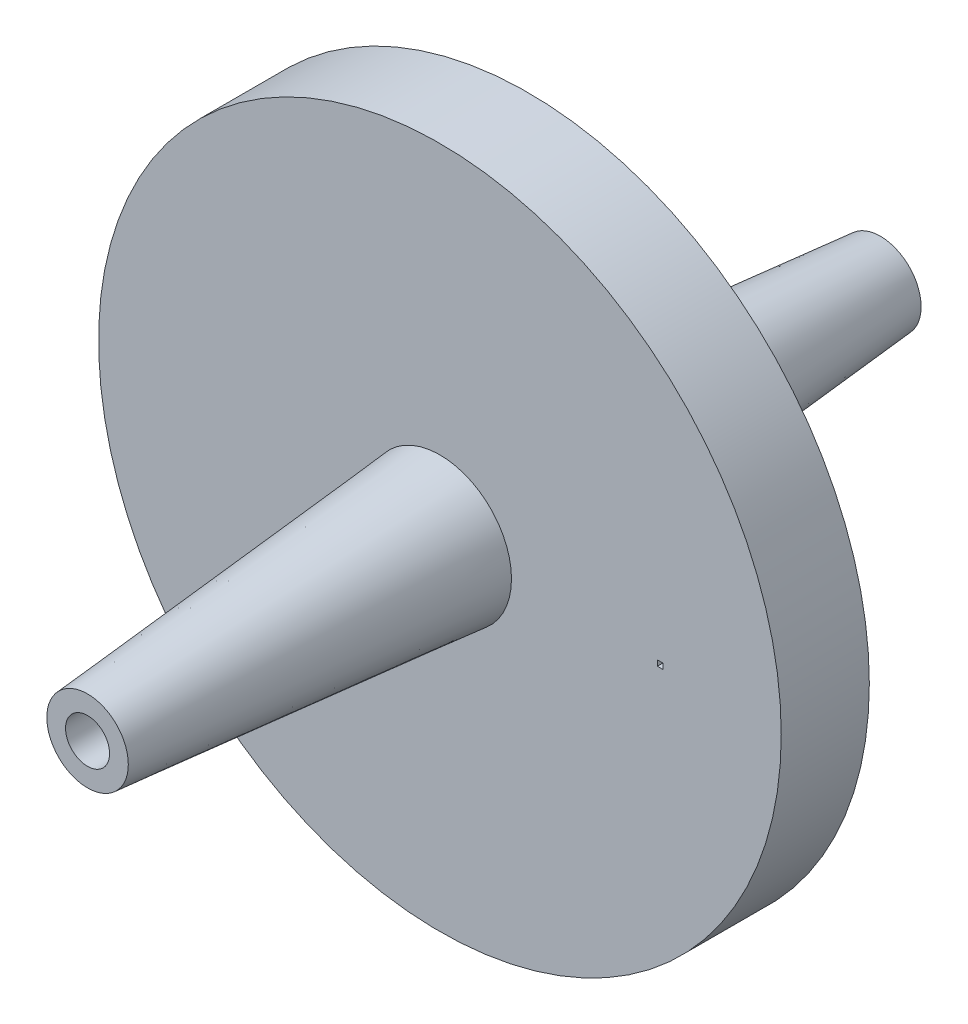
SolidWorks part; units mm, degrees
ref_plane "Front Plane" through (0, 0, 0) normal (0, 0, 1) x (1, 0, 0)
ref_plane "Top Plane" through (0, 0, 0) normal (0, 1, 0) x (1, 0, 0)
ref_plane "Right Plane" through (0, 0, 0) normal (1, 0, 0) x (0, 0, -1)
sketch "Sketch1" plane through (0, 0, 0) normal (0, 0, 1) x (1, 0, 0)
  circle A0 centre (0, 0) radius 31
  dimension "D1" = 62
extrude "Boss-Extrude1" add sketch "Sketch1" along normal mid plane 8
sketch "Sketch3" plane through (0, 0, 4) normal (0, 0, 1) x (1, 0, 0)
  circle A0 centre (0, 0) radius 6.5
  dimension "D1" = 13
extrude "Boss-Extrude2" add sketch "Sketch3" along normal blind 32 draft 5
mirror "Mirror1" about plane through (0, 0, 0) normal (0, 0, 1) of "Boss-Extrude2"
sketch "Sketch4" plane through (0, 0, 36) normal (0, 0, 1) x (1, 0, 0)
  circle A0 centre (0, 0) radius 2
  dimension "D1" = 4
extrude "Cut-Extrude1" cut sketch "Sketch4" against normal through all
sketch "Sketch5" plane through (0, 0, 4) normal (0, 0, 1) x (1, 0, 0)
  line L0 (0, 0) -> (20, 0) construction
  line L2 (19.75, 0.25) -> (20.25, 0.25)
  line L3 (19.75, 0.25) -> (19.75, -0.25)
  line L4 (19.75, -0.25) -> (20.25, -0.25)
  line L5 (20.25, 0.25) -> (20.25, -0.25)
  line L6 (19.75, 0.25) -> (20.25, -0.25) construction
  line L7 (19.75, -0.25) -> (20.25, 0.25) construction
  dimension "D1" = 20
  dimension "D2" = 0.5
  dimension "D3" = 0.5
extrude "Cut-Extrude2" cut sketch "Sketch5" against normal blind 0.5
